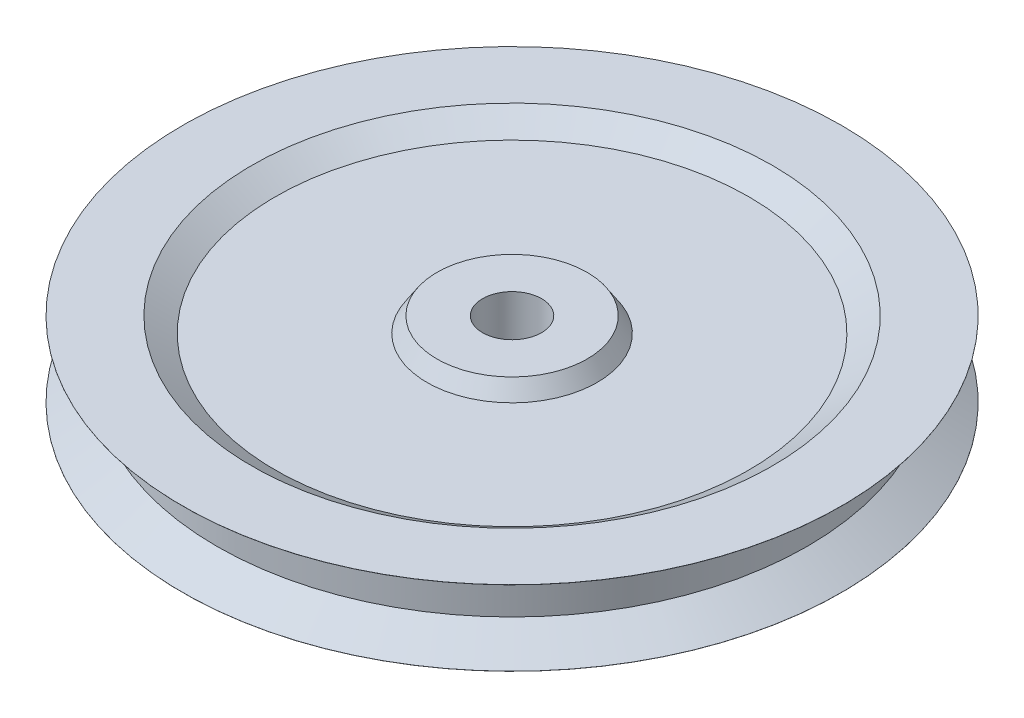
SolidWorks part; units mm, degrees
ref_plane "Alzado" through (0, 0, 0) normal (0, 0, 1) x (1, 0, 0)
ref_plane "Planta" through (0, 0, 0) normal (0, 1, 0) x (1, 0, 0)
ref_plane "Vista lateral" through (0, 0, 0) normal (1, 0, 0) x (0, 0, -1)
sketch "Croquis1" plane through (0, 0, 0) normal (0, 0, 1) x (1, 0, 0)
  line L0 (0, 0) -> (0, 34.081) construction
  line L1 (0, 0) -> (100, 0) construction
  line L2 (100, 5) -> (100, -5)
  line L3 (100, -5) -> (111.6504, -12.6708)
  line L4 (111.6504, -12.6708) -> (111.6504, -12.7)
  line L5 (111.6504, -12.7) -> (88.2022, -12.7)
  line L6 (88.2022, -12.7) -> (80.212, -7.5)
  line L7 (80.212, -7.5) -> (28.8281, -7.5)
  line L8 (28.8281, -7.5) -> (25.444, -12.7)
  line L9 (25.444, -12.7) -> (10, -12.7)
  line L10 (10, -12.7) -> (10, 12.7)
  line L11 (25.444, 12.7) -> (10, 12.7)
  line L12 (28.8281, 7.5) -> (25.444, 12.7)
  line L13 (80.212, 7.5) -> (28.8281, 7.5)
  line L14 (88.2022, 12.7) -> (80.212, 7.5)
  line L15 (111.6504, 12.7) -> (88.2022, 12.7)
  line L16 (111.6504, 12.6708) -> (111.6504, 12.7)
  line L17 (100, 5) -> (111.6504, 12.6708)
  point P7 (100, 0)
  point P15 (10, 0)
  point P22 (111.6504, -12.6708)
  dimension "D1" = 100
  dimension "D2" = 10
  dimension "D3" = 10
  dimension "D4" = 25.4
  dimension "D5" = 15
  dimension "D6" = 25.4
ref_axis "Eje1" through (0, -23.8365, 0) along (0, 1, 0)
revolve "Revolución1" add sketch "Croquis1" angle 360 about axis through (0, -23.8365, 0) along (0, 1, 0)
sketch "Croquis2" plane through (0, -12.7, 0) normal (0, -1, 0) x (1, 0, 0)
  circle A0 centre (0, 0) radius 10
  circle A1 centre (0, 0) radius 25.444
extrude "Saliente-Extruir1" add sketch "Croquis2" along normal blind 20
